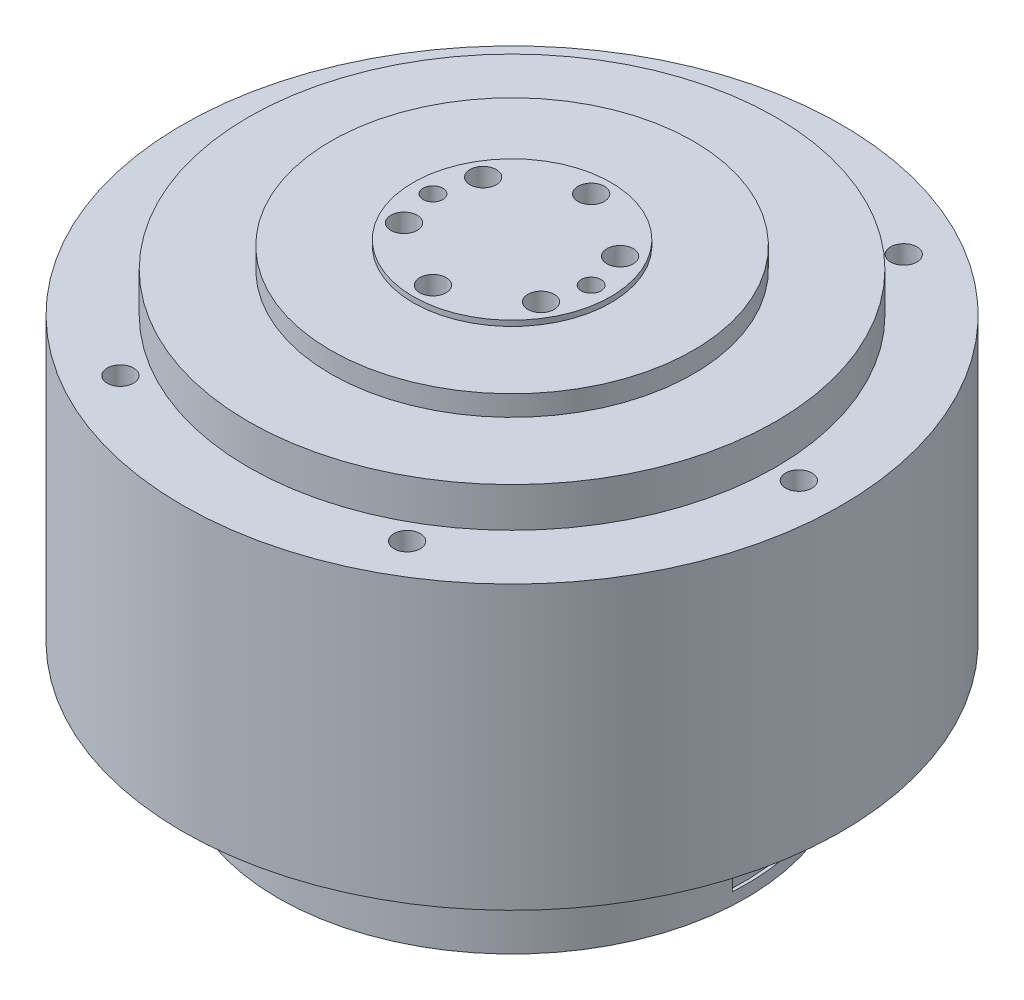
SolidWorks part; units mm, degrees
material "1023 Carbon Steel Sheet (SS)"
ref_plane "Front Plane" through (0, 0, 0) normal (0, 0, 1) x (1, 0, 0)
ref_plane "Top Plane" through (0, 0, 0) normal (0, 1, 0) x (1, 0, 0)
ref_plane "Right Plane" through (0, 0, 0) normal (1, 0, 0) x (0, 0, -1)
sketch "Sketch2" plane through (0, 0, 0) normal (0, 1, 0) x (1, 0, 0)
  circle A0 centre (0, 0) radius 35.5
  dimension "D1" = 71
extrude "Boss-Extrude1" add sketch "Sketch2" along normal blind 16
sketch "Sketch3" plane through (0, 16, 0) normal (0, 1, 0) x (1, 0, 0)
  circle A0 centre (0, 0) radius 50
  dimension "D1" = 100
extrude "Boss-Extrude2" add sketch "Sketch3" along normal blind 42.86
sketch "Sketch4" plane through (0, 58.86, 0) normal (0, 1, 0) x (1, 0, 0)
  circle A0 centre (0, 0) radius 40
  dimension "D1" = 80
extrude "Boss-Extrude3" add sketch "Sketch4" along normal blind 6
sketch "Sketch5" plane through (0, 64.86, 0) normal (0, 1, 0) x (1, 0, 0)
  circle A0 centre (0, 0) radius 27.5
  dimension "D1" = 55
extrude "Boss-Extrude4" add sketch "Sketch5" along normal blind 3.1
sketch "Sketch6" plane through (0, 67.96, 0) normal (0, 1, 0) x (1, 0, 0)
  circle A0 centre (0, 0) radius 15
  dimension "D1" = 30
extrude "Boss-Extrude5" add sketch "Sketch6" along normal blind 0.82
sketch "Sketch7" plane through (0, 68.78, 0) normal (0, 1, 0) x (1, 0, 0)
  circle A0 centre (0, 0) radius 12 construction
  circle A1 centre (12, 0) radius 1.5
  circle A2 centre (-12, 0) radius 1.5
  dimension "D1" = 24
  dimension "D2" = 3
extrude "Cut-Extrude1" cut sketch "Sketch7" against normal blind 3
sketch "Sketch8" plane through (0, 68.78, 0) normal (0, 1, 0) x (1, 0, 0)
  line L0 (12, 0) -> (0, 0) construction
  line L1 (0, 0) -> (10.3923, -6) construction
  circle A0 centre (0, 0) radius 12 construction
  circle A1 centre (10.3923, -6) radius 2
  circle A2 centre (0, -12) radius 2
  circle A3 centre (-10.3923, -6) radius 2
  circle A4 centre (-10.3923, 6) radius 2
  circle A5 centre (0, 12) radius 2
  circle A6 centre (10.3923, 6) radius 2
  dimension "D1" = 24
  dimension "D2" = 4
  dimension "D3" = 6
  dimension "D4" = 30
extrude "Cut-Extrude2" cut sketch "Sketch8" against normal blind 8
sketch "Sketch9" plane through (0, 58.86, 0) normal (0, 1, 0) x (1, 0, 0)
  line L0 (43.5, 0) -> (0, 0) construction
  circle A0 centre (0, 0) radius 43.5 construction
  circle A1 centre (43.5, 0) radius 2
  circle A2 centre (21.75, -37.6721) radius 2
  circle A3 centre (-21.75, -37.6721) radius 2
  circle A4 centre (-43.5, 0) radius 2
  circle A5 centre (-21.75, 37.6721) radius 2
  circle A6 centre (21.75, 37.6721) radius 2
  dimension "D1" = 87
  dimension "D2" = 4
  dimension "D3" = 6
extrude "Cut-Extrude3" cut sketch "Sketch9" against normal blind 8.5
sketch "Sketch10" plane through (0, 16, 0) normal (0, -1, 0) x (1, 0, 0)
  circle A0 centre (0, 0) radius 43.5 construction
  circle A1 centre (-43.5, 0) radius 2
  circle A2 centre (-21.75, 37.6721) radius 2
  circle A3 centre (21.75, 37.6721) radius 2
  circle A4 centre (43.5, 0) radius 2
  circle A5 centre (21.75, -37.6721) radius 2
  circle A6 centre (-21.75, -37.6721) radius 2
  dimension "D1" = 4
  dimension "D3" = 87
  dimension "D2" = 6
extrude "Cut-Extrude4" cut sketch "Sketch10" against normal blind 4.5
sketch "Sketch12" plane through (0, 0, 0) normal (1, 0, 0) x (0, 0, -1)
  line L0 (-35.5, 0) -> (35.5, 0) construction
  line L1 (-2, 12.8) -> (20, 12.8)
  line L2 (-2, 12.8) -> (-2, 1.8)
  line L3 (-2, 1.8) -> (20, 1.8)
  line L4 (20, 12.8) -> (20, 1.8)
  line L5 (-2, 20.5) -> (-2, 16) construction
  dimension "D1" = 22
  dimension "D2" = 1.8
  dimension "D3" = 11
extrude "Cut-Extrude6" cut sketch "Sketch12" along normal blind 54.5
sketch "Sketch13" plane through (0, 0, 0) normal (1, 0, 0) x (0, 0, -1)
  line L0 (1.4251, 10.6195) -> (1.4251, 12.8)
  line L1 (-2, 9.2162) -> (-2, 1.8)
  line L2 (12.0358, 11.49) -> (12.0358, 12.8)
  line L3 (14.6558, 12.8) -> (14.6558, 11.49)
  line L4 (-2, 12.8) -> (-2, 1.8)
  line L5 (-2, 1.8) -> (20, 1.8)
  line L6 (20, 1.8) -> (20, 12.8)
  line L7 (20, 12.8) -> (-2, 12.8)
  line L9 (-2, 1.8) -> (20, 1.8)
  line L10 (20, 1.8) -> (20, 12.8)
  line L11 (20, 12.8) -> (14.6558, 12.8)
  line L12 (12.0358, 12.8) -> (1.4251, 12.8)
  arc A0 (12.0358, 11.49) -> (14.6558, 11.49) centre (13.3458, 11.49) ccw
  arc A1 (-2, 9.2162) -> (1.4251, 10.6195) centre (-0.5749, 10.6195) ccw
  dimension "D2" = 4
  dimension "D3" = 1.31
  dimension "D6" = 7.4162
  dimension "D7" = 2.1805
  dimension "D4" = 5.3442
  dimension "D5" = 10.6106
  dimension "D1" = 0
extrude "Boss-Extrude6" add sketch "Sketch13" along normal offset from surface (34.9428 mm away) 0.5
ref_point "Point1"
ref_point "Point3"
ref_plane "Plane1" through (0, 0, 0) normal (0.5, 0, 0.866) x (0.866, 0, -0.5)
ref_point "Point4"
ref_point "Point5"
ref_plane "Plane2" through (0, 0, 0) normal (-0.866, 0, 0.5) x (0.5, 0, 0.866)
